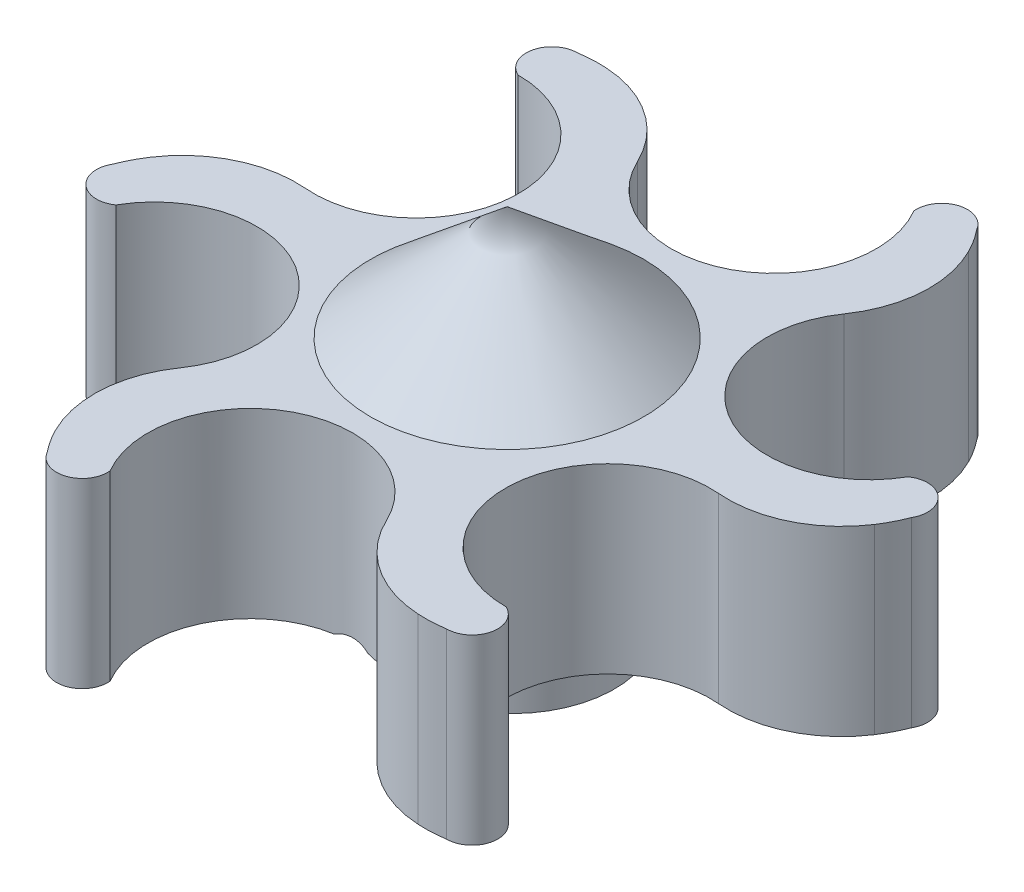
SolidWorks part; units mm, degrees
ref_plane "Front Plane" through (0, 0, 0) normal (0, 0, 1) x (1, 0, 0)
ref_plane "Top Plane" through (0, 0, 0) normal (0, 1, 0) x (1, 0, 0)
ref_plane "Right Plane" through (0, 0, 0) normal (1, 0, 0) x (0, 0, -1)
sketch "Sketch1" plane through (0, 0, 0) normal (0, 1, 0) x (1, 0, 0)
  circle A0 centre (0, 0) radius 9 construction
  arc A1 (-22.8067, 2.976) -> (-22.8067, -2.976) centre (0, 0) ccw
  arc A2 (-8.8261, 21.2391) -> (8.8261, 21.2391) centre (0, 23) ccw
  arc A3 (13.9806, 18.2632) -> (22.8067, 2.976) centre (19.9186, 11.5) ccw
  arc A4 (22.8067, -2.976) -> (13.9806, -18.2632) centre (19.9186, -11.5) ccw
  arc A5 (8.8261, -21.2391) -> (-8.8261, -21.2391) centre (0, -23) ccw
  arc A6 (-13.9806, -18.2632) -> (-22.8067, -2.976) centre (-19.9186, -11.5) ccw
  arc A7 (-22.8067, 2.976) -> (-13.9806, 18.2632) centre (-19.9186, 11.5) ccw
  arc A8 (-8.8261, 21.2391) -> (-13.9806, 18.2632) centre (0, 0) ccw
  arc A9 (13.9806, 18.2632) -> (8.8261, 21.2391) centre (0, 0) ccw
  arc A10 (22.8067, -2.976) -> (22.8067, 2.976) centre (0, 0) ccw
  arc A11 (8.8261, -21.2391) -> (13.9806, -18.2632) centre (0, 0) ccw
  arc A12 (-13.9806, -18.2632) -> (-8.8261, -21.2391) centre (0, 0) ccw
  point P18 (0, 0)
  dimension "D1" = 18
  dimension "D2" = 46
  dimension "D3" = 18
  dimension "D4" = 6
extrude "Boss-Extrude1" add sketch "Sketch1" along normal blind 16
sketch "Sketch2" plane through (0, 16, 0) normal (0, 1, 0) x (1, 0, 0)
  circle A0 centre (0, 23) radius 9 construction
  circle A1 centre (-19.9186, 11.5) radius 9 construction
  arc A2 (-13.9806, 18.2632) -> (-19.9806, 20.4998) centre (-19.9186, 11.5) ccw
  arc A3 (-19.0409, 24.7942) -> (-19.9806, 20.4998) centre (-19.0409, 22.5442) ccw
  arc A4 (-8.8261, 21.2391) -> (-19.0409, 24.7942) centre (-17.285, 13.3867) ccw
  arc A5 (-8.8261, 21.2391) -> (-13.9806, 18.2632) centre (0, 0) ccw construction
  arc A6 (-8.8261, 21.2391) -> (-13.9806, 18.2632) centre (0, 0) ccw
  arc A7 (13.9806, 18.2632) -> (8.8261, 21.2391) centre (0, 0) ccw
  arc A8 (8.8261, 21.2391) -> (7.763, 27.5536) centre (0, 23) ccw
  arc A9 (11.9519, 28.887) -> (7.763, 27.5536) centre (10.0034, 27.762) ccw
  arc A10 (13.9806, 18.2632) -> (11.9519, 28.887) centre (2.9507, 21.6626) ccw
  arc A11 (22.8067, -2.976) -> (22.8067, 2.976) centre (0, 0) ccw
  arc A12 (22.8067, 2.976) -> (27.7436, 7.0538) centre (19.9186, 11.5) ccw
  arc A13 (30.9928, 4.0928) -> (27.7436, 7.0538) centre (29.0443, 5.2178) ccw
  arc A14 (22.8067, -2.976) -> (30.9928, 4.0928) centre (20.2357, 8.2759) ccw
  arc A15 (8.8261, -21.2391) -> (13.9806, -18.2632) centre (0, 0) ccw
  arc A16 (13.9806, -18.2632) -> (19.9806, -20.4998) centre (19.9186, -11.5) ccw
  arc A17 (19.0409, -24.7942) -> (19.9806, -20.4998) centre (19.0409, -22.5442) ccw
  arc A18 (8.8261, -21.2391) -> (19.0409, -24.7942) centre (17.285, -13.3867) ccw
  arc A19 (-13.9806, -18.2632) -> (-8.8261, -21.2391) centre (0, 0) ccw
  arc A20 (-8.8261, -21.2391) -> (-7.763, -27.5536) centre (0, -23) ccw
  arc A21 (-11.9519, -28.887) -> (-7.763, -27.5536) centre (-10.0034, -27.762) ccw
  arc A22 (-13.9806, -18.2632) -> (-11.9519, -28.887) centre (-2.9507, -21.6626) ccw
  arc A23 (-22.8067, 2.976) -> (-22.8067, -2.976) centre (0, 0) ccw
  arc A24 (-22.8067, -2.976) -> (-27.7436, -7.0538) centre (-19.9186, -11.5) ccw
  arc A25 (-30.9928, -4.0928) -> (-27.7436, -7.0538) centre (-29.0443, -5.2178) ccw
  arc A26 (-22.8067, 2.976) -> (-30.9928, -4.0928) centre (-20.2357, -8.2759) ccw
  point P55 (0, 0)
  dimension "D1" = 4.5
  dimension "D2" = 6
  dimension "D3" = 6
extrude "Boss-Extrude2" add sketch "Sketch2" against normal up to surface (16 mm away) up to face at (0, 0, 0)
fillet "Fillet1" radius 10 6 edges at (-8.8261, 8, -21.2391) (13.9806, 8, -18.2632) (22.8067, 8, 2.976) (8.8261, 8, 21.2391) (-22.8067, 8, -2.976) (-13.9806, 8, 18.2632)
sketch "Sketch3" plane through (0, 0, 0) normal (0, -1, 0) x (1, 0, 0)
  circle A0 centre (0, 0) radius 9 construction
  circle A1 centre (0, 0) radius 9
extrude "Boss-Extrude3" add sketch "Sketch3" along normal blind 6
sketch "Sketch5" plane through (0, 0, 0) normal (0, 0, 1) x (1, 0, 0)
  line L0 (-9, -6) -> (9, -6) construction
  circle A0 centre (0, -2.436) radius 1.65
  dimension "D1" = 3.3
  dimension "D2" = 3.564
extrude "Cut-Extrude1" cut sketch "Sketch5" against normal through all and the other way through all
sketch "Sketch6" plane through (0, 0, 0) normal (0, 0, 1) x (1, 0, 0)
  line L0 (-0.4265, 16) -> (-0.4265, 26)
  line L1 (8.147, 16) -> (-9, 16) construction
  line L2 (-0.4265, 26) -> (11.5735, 16)
  line L3 (11.5735, 16) -> (-0.4265, 16)
  point P4 (8.282, 16)
  point P7 (12.0893, 16)
  dimension "D1" = 12
  dimension "D2" = 10
revolve "Revolve1" add sketch "Sketch6" angle 360 about L0
ref_plane "Plane3" through (0, 0, 9) normal (0, 0, 1) x (1, 0, 0)
sketch "Sketch10" plane through (0, 0, 9) normal (0, 0, 1) x (1, 0, 0)
  circle A0 centre (0, -2.436) radius 2.85
  dimension "D1" = 5.7
extrude "Cut-Extrude4" cut sketch "Sketch10" along normal through all
mirror "Mirror1" about plane through (0, 0, 0) normal (0, 0, 1) of "Cut-Extrude4"
